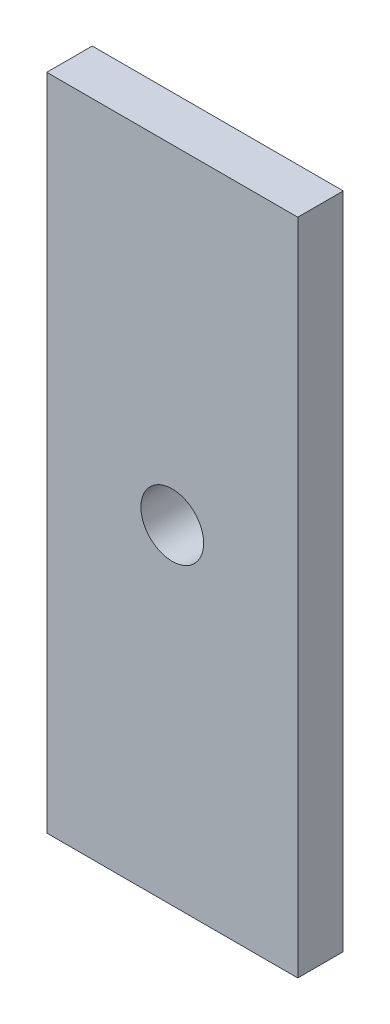
SolidWorks part; units mm, degrees
material "Бальса"
ref_plane "Спереди" through (0, 0, 0) normal (0, 0, 1) x (1, 0, 0)
ref_plane "Сверху" through (0, 0, 0) normal (0, 1, 0) x (1, 0, 0)
ref_plane "Справа" through (0, 0, 0) normal (1, 0, 0) x (0, 0, -1)
sketch "Эскиз1" plane through (0, 0, 0) normal (0, 0, 1) x (1, 0, 0)
  line L0 (16, 84) -> (16, 0) construction
  line L1 (0, 0) -> (32, 0)
  line L2 (0, 0) -> (0, 84)
  line L3 (0, 84) -> (32, 84)
  line L4 (32, 0) -> (32, 84)
  circle A0 centre (16, 42) radius 4
  dimension "D3" = 8
  dimension "D1" = 84
  dimension "D2" = 32
extrude "Бобышка-Вытянуть1" add sketch "Эскиз1" along normal blind 5.8
